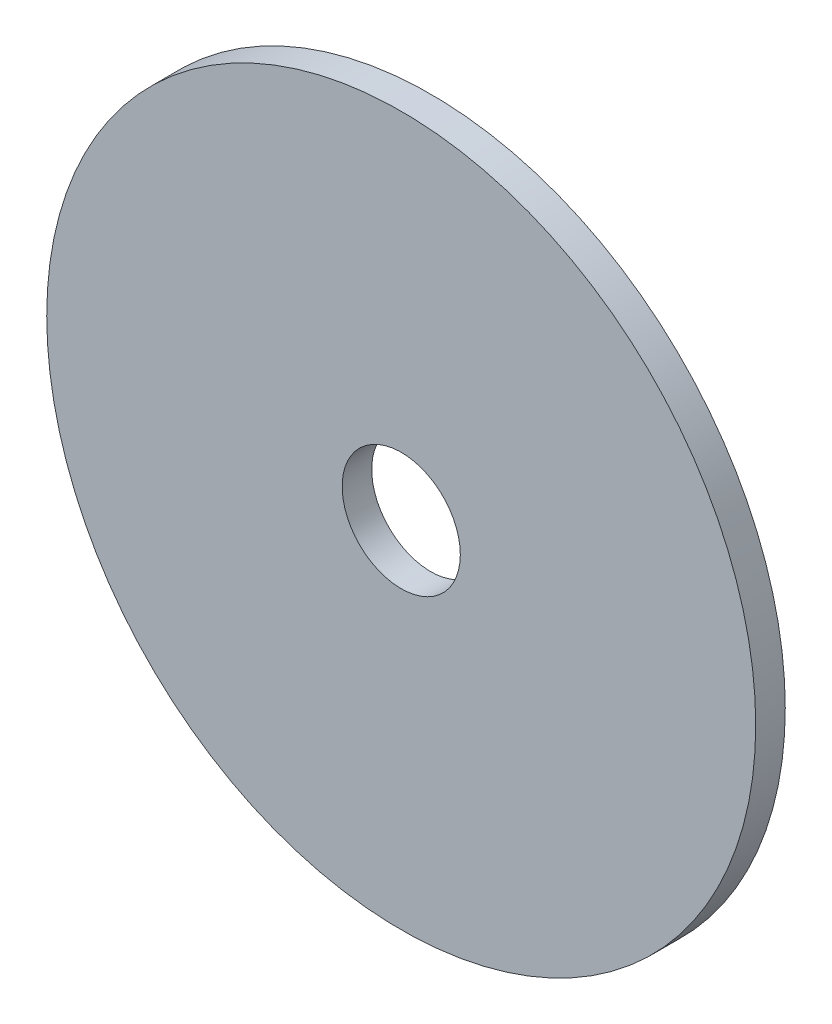
SolidWorks part; units mm, degrees
ref_plane "Front Plane" through (0, 0, 0) normal (0, 0, 1) x (1, 0, 0)
ref_plane "Top Plane" through (0, 0, 0) normal (0, 1, 0) x (1, 0, 0)
ref_plane "Right Plane" through (0, 0, 0) normal (1, 0, 0) x (0, 0, -1)
sketch "Sketch2" plane through (0, 0, 0) normal (0, 0, 1) x (1, 0, 0)
  circle A0 centre (0, 0) radius 38.1
  dimension "D1" = 76.2
extrude "Boss-Extrude1" add sketch "Sketch2" along normal blind 3.175
sketch "Sketch3" plane through (0, 0, 3.175) normal (0, 0, 1) x (1, 0, 0)
  circle A0 centre (0, 0) radius 6.35
  dimension "D1" = 12.7
extrude "Cut-Extrude1" cut sketch "Sketch3" against normal up to next
